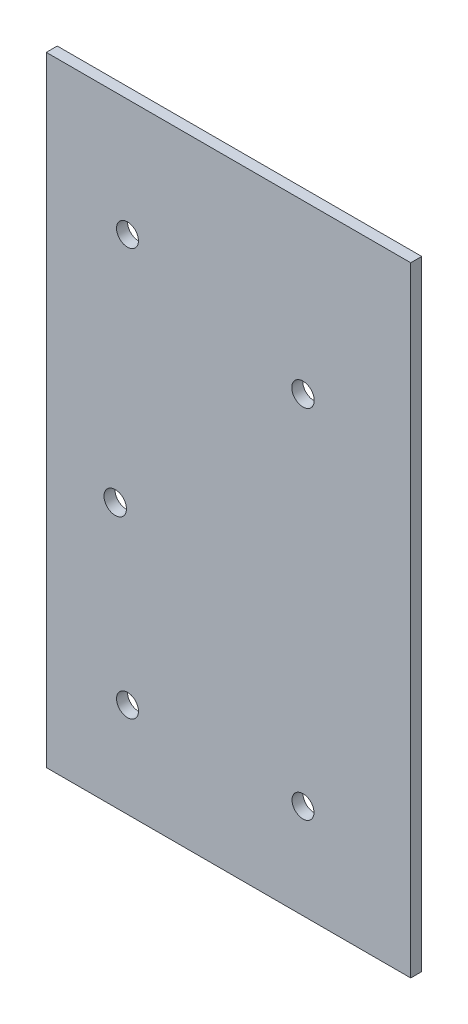
SolidWorks part; units mm, degrees
ref_plane "Front Plane" through (0, 0, 0) normal (0, 0, 1) x (1, 0, 0)
ref_plane "Top Plane" through (0, 0, 0) normal (0, 1, 0) x (1, 0, 0)
ref_plane "Right Plane" through (0, 0, 0) normal (1, 0, 0) x (0, 0, -1)
sketch "Sketch1" plane through (0, 0, 0) normal (0, 0, 1) x (1, 0, 0)
  line L0 (88.9, 95.25) -> (38.1, 95.25) construction
  line L1 (1.8891, 210.8161) -> (107.3869, 210.8161)
  line L2 (1.8891, 210.8161) -> (1.8891, 31.5173)
  line L3 (1.8891, 31.5173) -> (107.3869, 31.5173)
  line L4 (107.3869, 210.8161) -> (107.3869, 31.5173)
  line L6 (38.1, 95.25) -> (38.1, 146.05) construction
  circle A0 centre (25.4, 58.9643) radius 3.175
  circle A1 centre (76.2, 58.9643) radius 3.175
  circle A2 centre (25.4, 176.8929) radius 3.175
  circle A4 centre (76.2, 162.306) radius 3.2512
  circle A6 centre (21.844, 107.95) radius 3.2512
  dimension "D1" = 6.35
  dimension "D6" = 6.5024
  dimension "D4" = 16.256
  dimension "D7" = 33.9233
  dimension "D8" = 23.5109
  dimension "D9" = 27.447
  dimension "D10" = 31.1869
  dimension "D2" = 38.1
  dimension "D3" = 16.256
  dimension "D5" = 12.7
extrude "Boss-Extrude1" add sketch "Sketch1" along normal blind 3.175
equation "\"80/20 to Center Hole\"= .64in"
equation "\"80/20 from Edge\"= 0.5in"
equation "\"D4@Sketch1\"=\"80/20 to Center Hole\""
equation "\"D3@Sketch1\"=\"80/20 to Center Hole\""
equation "\"D5@Sketch1\"=\"80/20 from Edge\""
